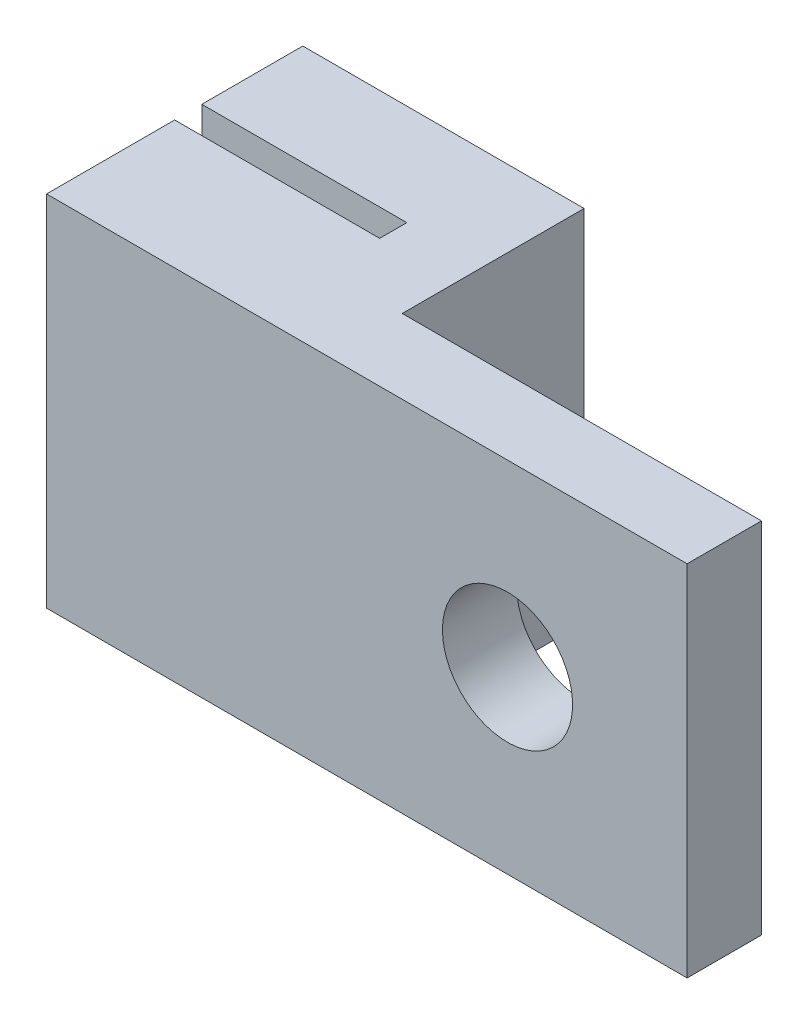
SolidWorks part; units mm, degrees
ref_plane "Front Plane" through (0, 0, 0) normal (0, 0, 1) x (1, 0, 0)
ref_plane "Top Plane" through (0, 0, 0) normal (0, 1, 0) x (1, 0, 0)
ref_plane "Right Plane" through (0, 0, 0) normal (1, 0, 0) x (0, 0, -1)
sketch "Sketch1" plane through (0, 0, 0) normal (0, 1, 0) x (1, 0, 0)
  line L1 (-1237.7101, -397.7364) -> (-1212.7101, -397.7364)
  line L2 (-1237.7101, -397.7364) -> (-1237.7101, -387.7364)
  line L3 (-1237.7101, -387.7364) -> (-1212.7101, -387.7364)
  line L4 (-1212.7101, -397.7364) -> (-1212.7101, -387.7364)
  line L5 (-1237.7101, -391.6764) -> (-1229.7101, -391.6764)
  line L6 (-1237.7101, -391.6764) -> (-1237.7101, -392.7364)
  line L7 (-1237.7101, -392.7364) -> (-1229.7101, -392.7364)
  line L8 (-1229.7101, -391.6764) -> (-1229.7101, -392.7364)
  dimension "D1" = 5
  dimension "D2" = 25
  dimension "D3" = 8
  dimension "D4" = 1.06
  dimension "D5" = 10
extrude "Boss-Extrude1" add sketch "Sketch1" against normal blind 14 contours L5 L8 L7 L2 L1 L4 L3
sketch "Sketch2" plane through (0, 0, 0) normal (0, 1, 0) x (1, 0, 0)
  line L0 (-1237.7101, -387.7364) -> (-1212.7101, -387.7364) construction
  line L1 (-1226.7298, -387.7364) -> (-1212.7101, -387.7364)
  line L2 (-1226.7298, -387.7364) -> (-1226.7298, -394.836)
  line L3 (-1226.7298, -394.836) -> (-1212.7101, -394.836)
  line L4 (-1212.7101, -387.7364) -> (-1212.7101, -394.836)
  line L5 (-1212.7101, -397.7364) -> (-1212.7101, -387.7364) construction
extrude "Cut-Extrude1" cut sketch "Sketch2" against normal through all
sketch "Sketch4" plane through (0, 0, 394.836) normal (0, 0, -1) x (-1, 0, 0)
  line L0 (1226.7298, 0) -> (1212.7101, 0) construction
  line L1 (1219.72, 0) -> (1219.72, -14) construction
  line L2 (1226.7298, -14) -> (1212.7101, -14) construction
  line L3 (1212.7101, -7) -> (1226.7298, -7) construction
  line L4 (1212.7101, -14) -> (1212.7101, 0) construction
  line L5 (1226.7298, -14) -> (1226.7298, 0) construction
  circle A0 centre (1219.72, -7) radius 2.54
  dimension "D1" = 5.08
extrude "Cut-Extrude2" cut sketch "Sketch4" against normal through all
